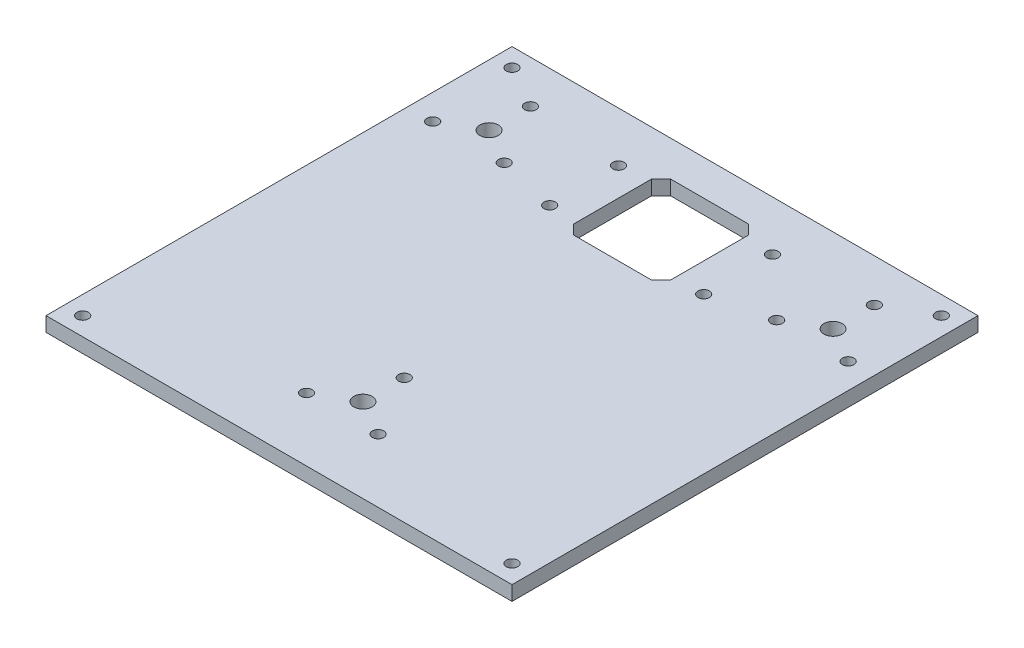
SolidWorks part; units mm, degrees
ref_plane "Plan de face" through (0, 0, 0) normal (0, 0, 1) x (1, 0, 0)
ref_plane "Plan de dessus" through (0, 0, 0) normal (0, 1, 0) x (1, 0, 0)
ref_plane "Plan de droite" through (0, 0, 0) normal (1, 0, 0) x (0, 0, -1)
sketch "Esquisse1" plane through (0, 0, 0) normal (0, 1, 0) x (1, 0, 0)
  line L1 (-101.6, -101.6) -> (101.6, -101.6)
  line L2 (-101.6, -101.6) -> (-101.6, 101.6)
  line L3 (-101.6, 101.6) -> (101.6, 101.6)
  line L4 (101.6, -101.6) -> (101.6, 101.6)
  line L5 (-101.6, -101.6) -> (101.6, 101.6) construction
  line L6 (-101.6, 101.6) -> (101.6, -101.6) construction
  point P0 (0, 0)
  dimension "D1" = 203.2
extrude "Boss.-Extru.1" add sketch "Esquisse1" along normal blind 6.35
sketch "Esquisse2" plane through (0, 6.35, 0) normal (0, 1, 0) x (1, 0, 0)
  circle A0 centre (-75, 65) radius 4
  circle A1 centre (75, 65) radius 4
  circle A2 centre (0, -65) radius 4
  dimension "D1" = 8
  dimension "D2" = 65
  dimension "D3" = 65
  dimension "D4" = 150
  dimension "D5" = 75
extrude "Enlèv. mat.-Extru.1" cut sketch "Esquisse2" against normal through all
sketch "Esquisse3" plane through (0, 6.35, 0) normal (0, 1, 0) x (1, 0, 0)
  line L0 (-17.05, 86.15) -> (-21.15, 82.05)
  line L1 (-21.15, 82.05) -> (-21.15, 47.95)
  line L2 (-21.15, 47.95) -> (-17.05, 43.85)
  line L3 (-17.05, 43.85) -> (17.05, 43.85)
  line L4 (17.05, 43.85) -> (21.15, 47.95)
  line L5 (21.15, 47.95) -> (21.15, 82.05)
  line L6 (21.15, 82.05) -> (17.05, 86.15)
  line L7 (17.05, 86.15) -> (-17.05, 86.15)
  line L9 (-75, 65) -> (75, 65) construction
  point P8 (0, 43.85)
  point P11 (0, 86.15)
  point P12 (-21.15, 65)
  point P13 (21.15, 65)
  dimension "D2" = 42.3
  dimension "D3" = 34.1
extrude "Enlèv. mat.-Extru.2" cut sketch "Esquisse3" against normal through all
sketch "Esquisse5" plane through (0, 6.35, 0) normal (0, 1, 0) x (1, 0, 0)
  circle A0 centre (-33.425, 49.85) radius 2.5
  circle A1 centre (-33.425, 79.85) radius 2.5
  circle A2 centre (33.725, 49.85) radius 2.5
  circle A3 centre (33.725, 79.85) radius 2.5
  circle A4 centre (33.725, 49.85) radius 2.5 construction
extrude "Enlèv. mat.-Extru.4" cut sketch "Esquisse5" against normal through all
sketch "Esquisse6" plane through (0, 6.35, 0) normal (0, 1, 0) x (1, 0, 0)
  line L0 (-101.6, -101.6) -> (101.6, -101.6) construction
  line L1 (101.6, -101.6) -> (101.6, 101.6) construction
  line L2 (-101.6, 101.6) -> (-101.6, -101.6) construction
  line L3 (101.6, 101.6) -> (-101.6, 101.6) construction
  circle A0 centre (93.6, -93.6) radius 2.5
  circle A1 centre (-93.6, -93.6) radius 2.5
  circle A2 centre (-93.6, 93.6) radius 2.5
  circle A3 centre (93.6, 93.6) radius 2.5
  dimension "D1" = 5
  dimension "D2" = 8
  dimension "D3" = 8
  dimension "D4" = 8
  dimension "D5" = 8
extrude "Enlèv. mat.-Extru.5" cut sketch "Esquisse6" against normal through all
sketch "Esquisse7" plane through (0, 6.35, 0) normal (0, 1, 0) x (1, 0, 0)
  circle A0 centre (-15.5885, -74) radius 2.5
  circle A1 centre (15.5885, -74) radius 2.5
  circle A2 centre (0, -47) radius 2.5
  circle A3 centre (90.5885, 56) radius 2.5
  circle A4 centre (59.4115, 56) radius 2.5
  circle A5 centre (75, 83) radius 2.5
  circle A6 centre (-90.5885, 56) radius 2.5
  circle A7 centre (-59.4115, 56) radius 2.5
  circle A8 centre (-75, 83) radius 2.5
extrude "Enlèv. mat.-Extru.6" cut sketch "Esquisse7" against normal through all
